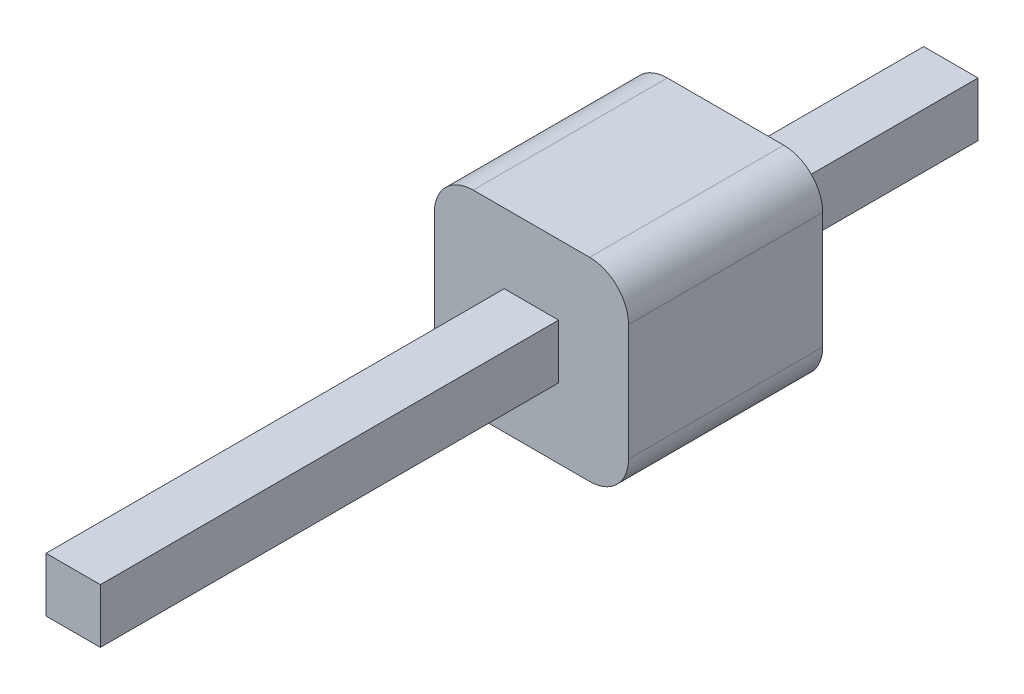
SolidWorks part; units mm, degrees
ref_plane "Alzado" through (0, 0, 0) normal (0, 0, 1) x (1, 0, 0)
ref_plane "Planta" through (0, 0, 0) normal (0, 1, 0) x (1, 0, 0)
ref_plane "Vista lateral" through (0, 0, 0) normal (1, 0, 0) x (0, 0, -1)
sketch "Croquis1" plane through (0, 0, 0) normal (0, 0, 1) x (1, 0, 0)
  line L1 (0.35, -0.35) -> (-0.35, -0.35)
  line L2 (0.35, -0.35) -> (0.35, 0.35)
  line L3 (0.35, 0.35) -> (-0.35, 0.35)
  line L4 (-0.35, -0.35) -> (-0.35, 0.35)
  line L5 (0.35, -0.35) -> (-0.35, 0.35) construction
  line L6 (0.35, 0.35) -> (-0.35, -0.35) construction
  point P0 (0, 0)
  dimension "D1" = 0.7
  dimension "D2" = 0.7
extrude "Saliente-Extruir1" add sketch "Croquis1" along normal blind 11.3
ref_plane "Plano1" through (0, 0, 2.9) normal (0, 0, -1) x (-1, 0, 0)
sketch "Croquis2" plane through (0, 0, 2.9) normal (0, 0, -1) x (-1, 0, 0)
  line L1 (1.25, -1.25) -> (-1.25, -1.25)
  line L2 (1.25, -1.25) -> (1.25, 1.25)
  line L3 (1.25, 1.25) -> (-1.25, 1.25)
  line L4 (-1.25, -1.25) -> (-1.25, 1.25)
  line L5 (1.25, -1.25) -> (-1.25, 1.25) construction
  line L6 (1.25, 1.25) -> (-1.25, -1.25) construction
  point P0 (0, 0)
  dimension "D1" = 2.5
  dimension "D2" = 2.5
extrude "Saliente-Extruir2" add sketch "Croquis2" against normal blind 2.5
fillet "Redondeo1" radius 0.5 4 edges at (-1.25, -1.25, 4.15) (-1.25, 1.25, 4.15) (1.25, 1.25, 4.15) (1.25, -1.25, 4.15)
